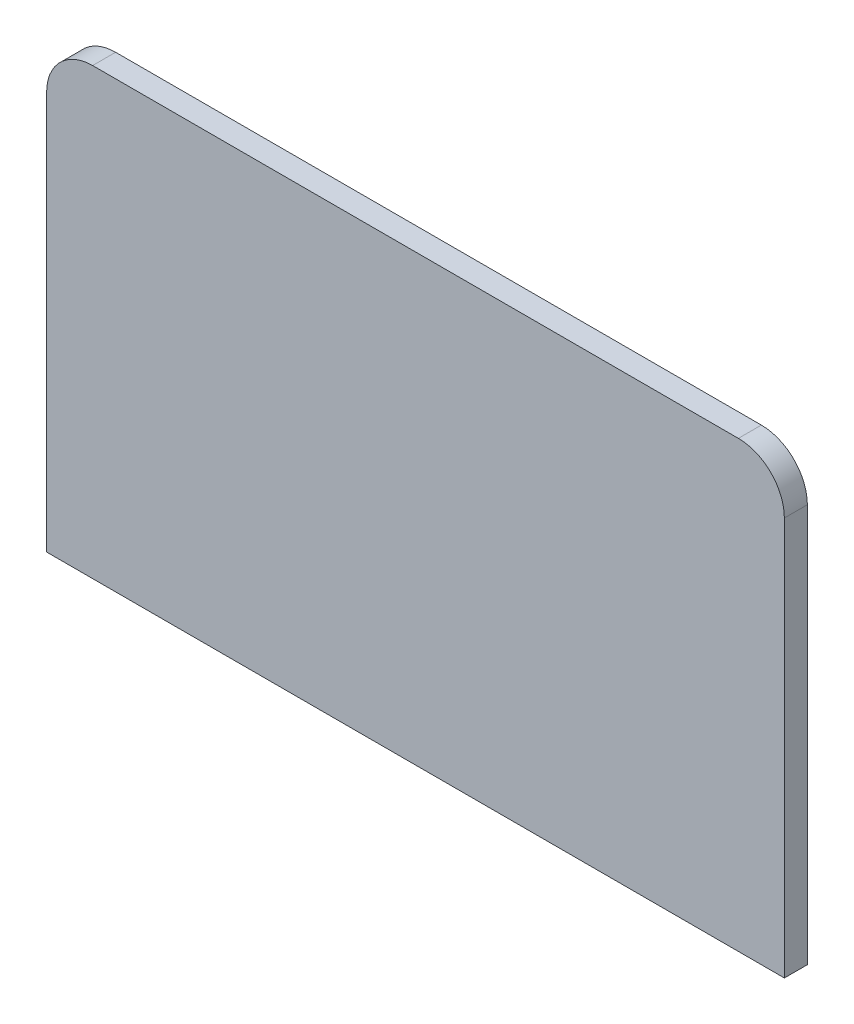
SolidWorks part; units mm, degrees
ref_plane "Front Plane" through (0, 0, 0) normal (0, 0, 1) x (1, 0, 0)
ref_plane "Top Plane" through (0, 0, 0) normal (0, 1, 0) x (1, 0, 0)
ref_plane "Right Plane" through (0, 0, 0) normal (1, 0, 0) x (0, 0, -1)
sketch "Sketch1" plane through (0, 0, 0) normal (0, 0, 1) x (1, 0, 0)
  line L0 (20.2074, -1520.6902) -> (20.2074, 1527.3098) construction
  line L1 (-183.5006, 1527.3098) -> (20.2074, 1527.3098)
  line L2 (-183.5006, 1527.3098) -> (-183.5006, 1404.61)
  line L3 (-183.5006, 1404.61) -> (20.2074, 1404.61)
  line L4 (20.2074, 1527.3098) -> (20.2074, 1404.61)
  arc A0 (-183.5006, 1404.61) -> (-584.7519, 1081.1932) centre (1309.6009, -858.4433) ccw construction
extrude "Boss-Extrude1" add sketch "Sketch1" along normal blind 6.35
fillet "Fillet1" radius 12.7 2 edges at (-183.5006, 1527.3098, 3.175) (20.2074, 1527.3098, 3.175)
